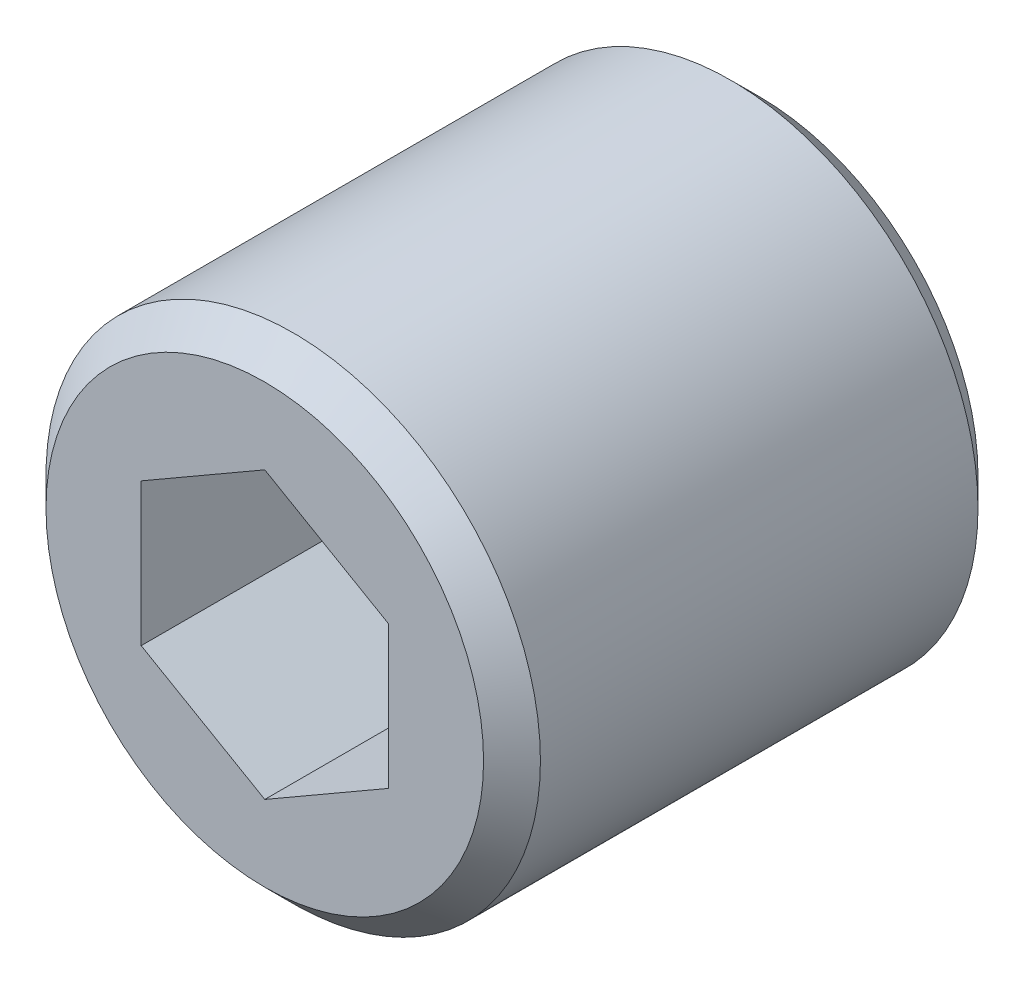
SolidWorks part; units mm, degrees
ref_plane "Płaszczyzna przednia" through (0, 0, 0) normal (0, 0, 1) x (1, 0, 0)
ref_plane "Płaszczyzna górna" through (0, 0, 0) normal (0, 1, 0) x (1, 0, 0)
ref_plane "Płaszczyzna prawa" through (0, 0, 0) normal (1, 0, 0) x (0, 0, -1)
ref_plane "Płaszczyzna1" through (0, 0, 8) normal (0, 0, 1) x (1, 0, 0)
sketch "Szkic1" plane through (0, 0, 0) normal (1, 0, 0) x (0, 0, -1)
  line L0 (-8, 0) -> (-8, 3.54)
  line L1 (-8, 3.54) -> (-7.54, 4)
  line L2 (-7.54, 4) -> (-0.46, 4)
  line L3 (-0.46, 4) -> (0, 3.54)
  line L4 (0, 3.54) -> (0, 0)
  line L5 (0, 0) -> (-8, 0)
  line L6 (0, 0) -> (-8, 0) construction
revolve "Obrót1" add sketch "Szkic1" angle 360 about L6
cosmetic thread "Oznaczenie gwintu1" parameters "D1"=8, "D2"=7.08
sketch "Szkic2" plane through (0, 0, 0) normal (1, 0, 0) x (0, 0, -1)
  line L0 (-8, 0) -> (-8, 2.8094)
  line L1 (-8, 2.8094) -> (-4, 2.8094)
  line L2 (-4, 2.8094) -> (-2.378, 0)
  line L3 (-2.378, 0) -> (-8, 0)
  line L4 (-2.378, 0) -> (-8, 0) construction
revolve "Wycięcie-obrót1" cut sketch "Szkic2" angle 360 about L4
sketch "Szkic3" plane through (0, 0, 8) normal (0, 0, 1) x (1, 0, 0)
  line L0 (-2, 1.1547) -> (-2, -1.1547)
  line L1 (-2, -1.1547) -> (0, -2.3094)
  line L2 (0, -2.3094) -> (2, -1.1547)
  line L3 (2, -1.1547) -> (2, 1.1547)
  line L4 (2, 1.1547) -> (0, 2.3094)
  line L5 (0, 2.3094) -> (-2, 1.1547)
  circle A0 centre (0, 0) radius 3.0094
extrude "Dodanie-wyciągnięcie1" add sketch "Szkic3" against normal blind 6
